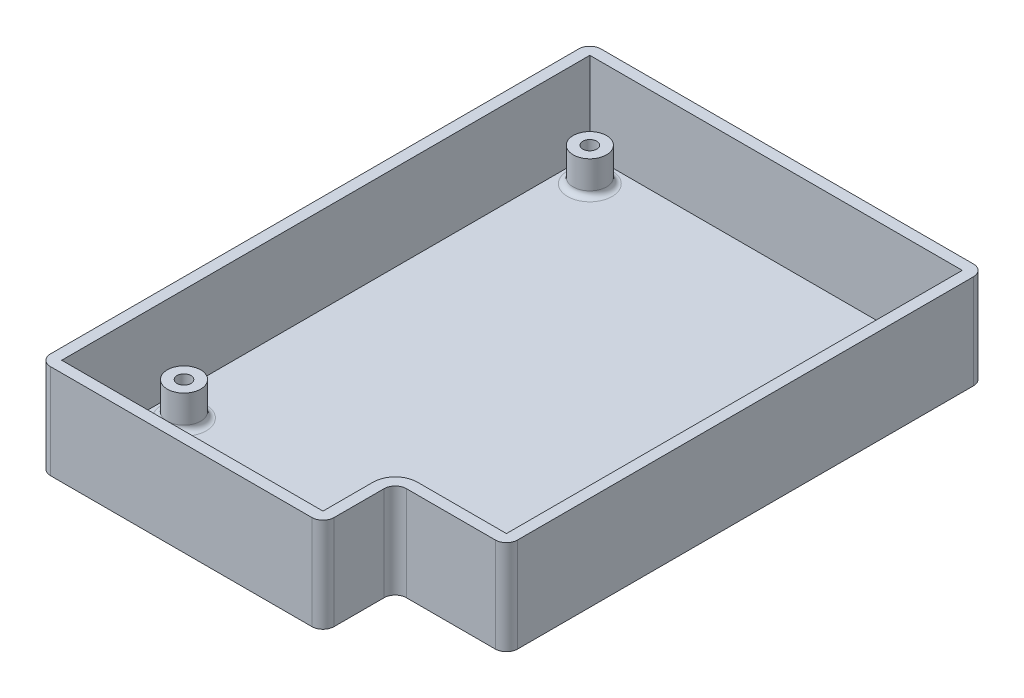
SolidWorks part; units mm, degrees
ref_plane "Спереди" through (0, 0, 0) normal (0, 0, 1) x (1, 0, 0)
ref_plane "Сверху" through (0, 0, 0) normal (0, 1, 0) x (1, 0, 0)
ref_plane "Справа" through (0, 0, 0) normal (1, 0, 0) x (0, 0, -1)
sketch "Sketch1" plane through (0, 0, 0) normal (0, 1, 0) x (1, 0, 0)
  line L0 (0, 0) -> (0, -6.5) construction
  line L1 (-29, -36.5) -> (29, -36.5) construction
  line L2 (-29, -36.5) -> (-29, 36.5) construction
  line L3 (-29, 36.5) -> (29, 36.5) construction
  line L4 (29, -36.5) -> (29, 36.5) construction
  line L5 (-29, -36.5) -> (29, 36.5) construction
  line L6 (-29, 36.5) -> (29, -36.5) construction
  line L7 (33.5, -54) -> (-33.5, -54) construction
  line L8 (33.5, -54) -> (33.5, 41) construction
  line L9 (33.5, 41) -> (-33.5, 41) construction
  line L10 (-33.5, -54) -> (-33.5, 41) construction
  line L11 (33.5, -54) -> (-33.5, 41) construction
  line L12 (33.5, 41) -> (-33.5, -54) construction
  line L13 (35.5, -56) -> (-35.5, -56) construction
  line L14 (35.5, 43) -> (35.5, -56) construction
  line L15 (35.5, 43) -> (-35.5, 43)
  line L16 (-35.5, -56) -> (-35.5, 43) construction
  line L17 (35.5, -56) -> (-35.5, 43) construction
  line L18 (35.5, 43) -> (-35.5, -56) construction
  line L19 (33.5, -41) -> (-33.5, -41) construction
  line L20 (15.5, -43) -> (35.5, -43) construction
  line L21 (13.5, -41) -> (13.5, -54) construction
  line L22 (15.5, -43) -> (15.5, -56) construction
  line L23 (-35.5, 43) -> (-35.5, -56)
  line L24 (-35.5, -56) -> (15.5, -56)
  line L25 (15.5, -56) -> (15.5, -43)
  line L26 (15.5, -43) -> (35.5, -43)
  line L27 (35.5, -43) -> (35.5, 43)
  point P0 (0, 0)
  point P6 (0, 0)
  point P11 (0, 0)
  dimension "D1" = 58
  dimension "D2" = 73
  dimension "D3" = 67
  dimension "D4" = 95
  dimension "D5" = 2
  dimension "D6" = 2
  dimension "D7" = 41
  dimension "D8" = 2
  dimension "D9" = 2
  dimension "D10" = 2
  dimension "D11" = 20
  dimension "D12" = 82
  dimension "D13" = 2
extrude "Boss-Extrude1" add sketch "Sketch1" along normal blind 1.5
sketch "Sketch3" plane through (0, 1.5, 0) normal (0, 1, 0) x (1, 0, 0)
  line L0 (0, 36.5) -> (0, -36.5) construction
  line L1 (-29, 36.5) -> (29, 36.5) construction
  line L2 (-29, -36.5) -> (29, -36.5) construction
  line L3 (-29, 0) -> (29, 0) construction
  line L4 (-29, -36.5) -> (-29, 36.5) construction
  line L5 (29, -36.5) -> (29, 36.5) construction
  circle A0 centre (-29, 36.5) radius 1.25
  circle A1 centre (-29, 36.5) radius 3
  circle A2 centre (29, 36.5) radius 1.25
  circle A3 centre (29, 36.5) radius 3
  circle A4 centre (29, -36.5) radius 1.25
  circle A5 centre (29, -36.5) radius 3
  circle A6 centre (-29, -36.5) radius 1.25
  circle A7 centre (-29, -36.5) radius 3
  dimension "D1" = 2.5
  dimension "D2" = 6
extrude "Boss-Extrude3" add sketch "Sketch3" along normal blind 6
fillet "Fillet2" radius 1 4 edges at (-29, 1.5, 33.5) (29, 1.5, 39.5) (29, 1.5, -39.5) (-29, 1.5, -33.5)
sketch "Sketch5" plane through (0, 1.5, 0) normal (0, 1, 0) x (1, 0, 0)
  line L0 (-35.5, 43) -> (-35.5, -56)
  line L1 (-35.5, -56) -> (15.5, -56)
  line L2 (15.5, -56) -> (15.5, -43)
  line L3 (15.5, -43) -> (35.5, -43)
  line L4 (35.5, -43) -> (35.5, 43)
  line L5 (35.5, 43) -> (-35.5, 43)
  line L6 (-33.5, 41) -> (-33.5, -54)
  line L7 (-33.5, -54) -> (13.5, -54)
  line L8 (13.5, -54) -> (13.5, -41)
  line L9 (13.5, -41) -> (33.5, -41)
  line L10 (33.5, -41) -> (33.5, 41)
  line L11 (33.5, 41) -> (-33.5, 41)
extrude "Boss-Extrude5" add sketch "Sketch5" along normal blind 15.5
fillet "Fillet6" radius 2 6 edges at (35.5, 8.5, -43) (-35.5, 8.5, -43) (35.5, 8.5, 43) (-35.5, 8.5, 56) (15.5, 8.5, 56) (15.5, 8.5, 43)
fillet "Fillet7" radius 4 1 edges at (13.5, 9.25, 41)
